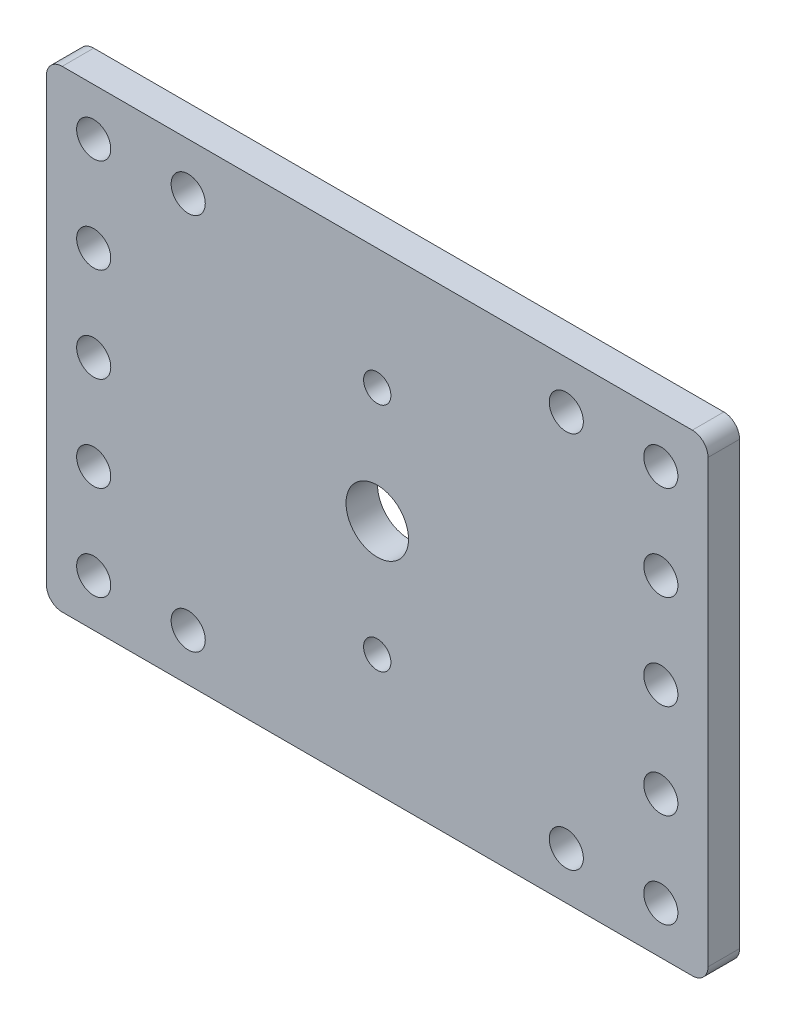
SolidWorks part; units mm, degrees
ref_plane "Alzado" through (0, 0, 0) normal (0, 0, 1) x (1, 0, 0)
ref_plane "Planta" through (0, 0, 0) normal (0, 1, 0) x (1, 0, 0)
ref_plane "Vista lateral" through (0, 0, 0) normal (1, 0, 0) x (0, 0, -1)
sketch "Model" plane through (0, 0, 0) normal (0, 0, 1) x (1, 0, 0)
  line L0 (194.7573, 257.2677) -> (254.7573, 257.2677)
  line L1 (256.2573, 255.7677) -> (256.2573, 213.7677)
  line L2 (254.7573, 212.2677) -> (194.7573, 212.2677)
  line L3 (193.2573, 213.7677) -> (193.2573, 255.7677)
  circle A0 centre (206.7573, 252.7677) radius 1.625
  circle A1 centre (206.7573, 216.7677) radius 1.625
  circle A2 centre (224.7573, 234.7677) radius 2.975
  circle A3 centre (242.7573, 252.7677) radius 1.625
  circle A4 centre (242.7573, 216.7677) radius 1.625
  arc A5 (194.7573, 257.2677) -> (193.2573, 255.7677) centre (194.7573, 255.7677) ccw
  arc A6 (256.2573, 255.7677) -> (254.7573, 257.2677) centre (254.7573, 255.7677) ccw
  arc A7 (193.2573, 213.7677) -> (194.7573, 212.2677) centre (194.7573, 213.7677) ccw
  arc A8 (254.7573, 212.2677) -> (256.2573, 213.7677) centre (254.7573, 213.7677) ccw
  circle A9 centre (224.7573, 223.7677) radius 1.3
  circle A10 centre (224.7573, 245.7677) radius 1.3
  circle A11 centre (197.7573, 252.7677) radius 1.625
  circle A12 centre (251.7573, 252.7677) radius 1.625
  circle A13 centre (251.7573, 216.7677) radius 1.625
  circle A14 centre (197.7573, 216.7677) radius 1.625
  circle A15 centre (197.7573, 234.7677) radius 1.625
  circle A16 centre (251.7573, 234.7677) radius 1.625
  circle A17 centre (197.7573, 243.7677) radius 1.625
  circle A18 centre (197.7573, 225.7677) radius 1.625
  circle A19 centre (251.7573, 243.7677) radius 1.625
  circle A20 centre (251.7573, 225.7677) radius 1.625
extrude "Saliente-Extruir1" add sketch "Model" along normal blind 3
